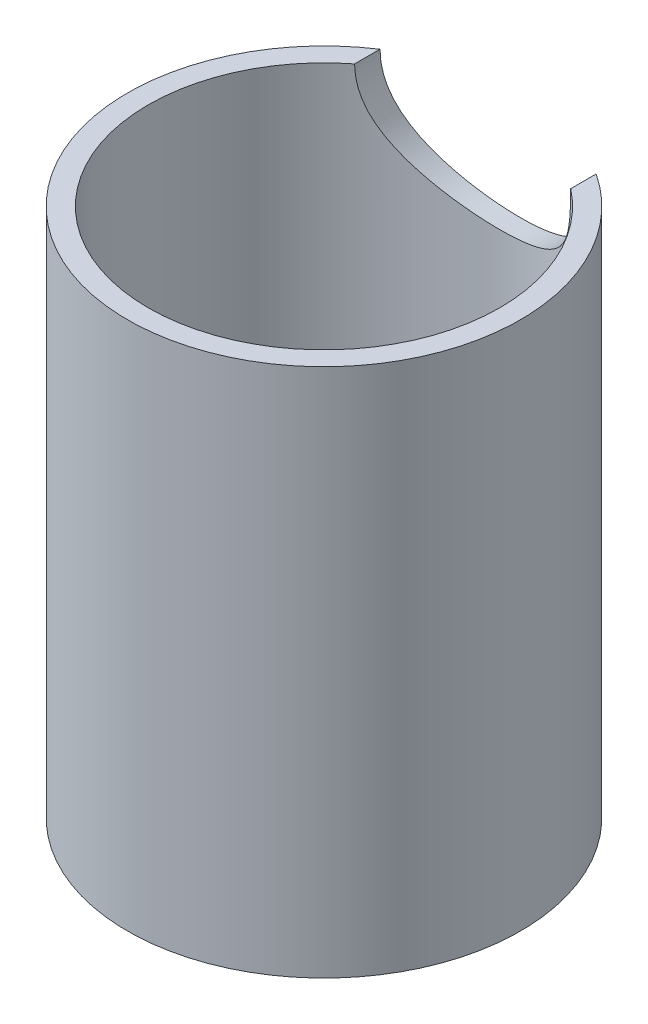
SolidWorks part; units mm, degrees
ref_plane "Front Plane" through (0, 0, 0) normal (0, 0, 1) x (1, 0, 0)
ref_plane "Top Plane" through (0, 0, 0) normal (0, 1, 0) x (1, 0, 0)
ref_plane "Right Plane" through (0, 0, 0) normal (1, 0, 0) x (0, 0, -1)
sketch "Sketch1" plane through (0, 0, 0) normal (0, 1, 0) x (1, 0, 0)
  circle A0 centre (0, 0) radius 19
  circle A1 centre (0, 0) radius 17
  dimension "D1" = 38
  dimension "D2" = 2
extrude "Boss-Extrude1" add sketch "Sketch1" along normal blind 51.2
sketch "Sketch2" plane through (0, 0, 0) normal (0, 0, 1) x (1, 0, 0)
  line L0 (19, 51.2) -> (-19, 51.2) construction
  circle A0 centre (0, 51.2) radius 10.45
  circle A1 centre (0, 0) radius 10.45
  dimension "D1" = 20.9
extrude "Cut-Extrude1" cut sketch "Sketch2" against normal through all
